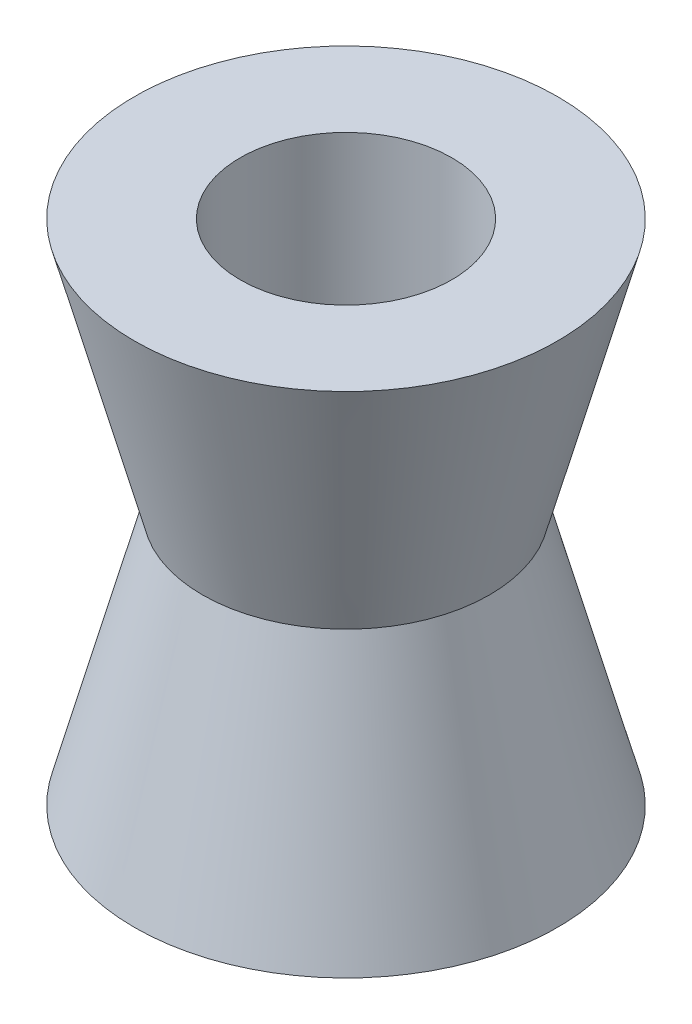
SolidWorks part; units mm, degrees
material "Plain Carbon Steel"
ref_plane "Front Plane" through (0, 0, 0) normal (0, 0, 1) x (1, 0, 0)
ref_plane "Top Plane" through (0, 0, 0) normal (0, 1, 0) x (1, 0, 0)
ref_plane "Right Plane" through (0, 0, 0) normal (1, 0, 0) x (0, 0, -1)
sketch "Sketch1" plane through (0, 0, 0) normal (0, 1, 0) x (1, 0, 0)
  circle A0 centre (0, 0) radius 50
  dimension "D1" = 100
extrude "Boss-Extrude1" add sketch "Sketch1" along normal blind 60 draft 15
mirror "Mirror1" [suppressed] about plane through (0, 0, 0) normal (0, 1, 0)
mirror "Mirror2" about plane through (0, 60, 0) normal (0, 1, 0) of "Boss-Extrude1"
sketch "Sketch2" plane through (0, 120, 0) normal (0, 1, 0) x (1, 0, 0)
  circle A3 centre (0, 0) radius 25
  dimension "D1" = 50
extrude "Cut-Extrude1" cut sketch "Sketch2" against normal through all both and the other way through all
equation "\"A\"= 120"
equation "\"B\"= 100"
equation "\"C\"= 15"
equation "\"D3@Boss-Extrude1\"=\"C\""
equation "\"D1@Sketch1\"=\"B\""
equation "\"D1@Boss-Extrude1\"=\"A\"/2"
